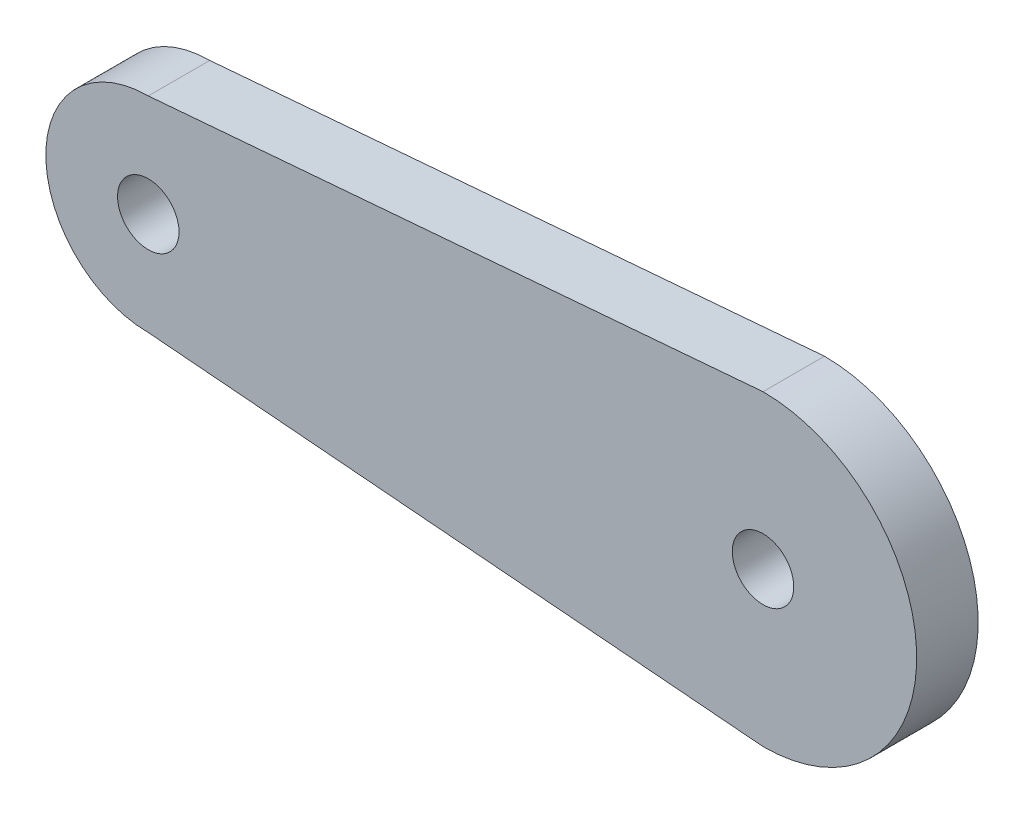
SolidWorks part; units mm, degrees
ref_plane "Front Plane" through (0, 0, 0) normal (0, 0, 1) x (1, 0, 0)
ref_plane "Top Plane" through (0, 0, 0) normal (0, 1, 0) x (1, 0, 0)
ref_plane "Right Plane" through (0, 0, 0) normal (1, 0, 0) x (0, 0, -1)
sketch "Sketch1" plane through (0, 0, 0) normal (0, 0, 1) x (1, 0, 0)
  line L0 (0, 0) -> (30, 0) construction
  line L1 (0, 5) -> (0, -5) construction
  line L2 (30, 7.5) -> (30, -7.5) construction
  line L3 (0, 5) -> (30, 7.5)
  line L4 (0, -5) -> (30, -7.5)
  circle A0 centre (0, 0) radius 1.5
  circle A1 centre (30, 0) radius 1.5
  arc A2 (0, 5) -> (0, -5) centre (0, 0) ccw
  arc A3 (30, 7.5) -> (30, -7.5) centre (30, 0) cw
  dimension "D5" = 5
  dimension "D6" = 3
  dimension "D7" = 3
  dimension "D1" = 30
  dimension "D2" = 10
  dimension "D3" = 15
  dimension "D4" = 7.5
extrude "Boss-Extrude1" add sketch "Sketch1" along normal blind 3 contours A3 L3 A2 L4 A1 A0
